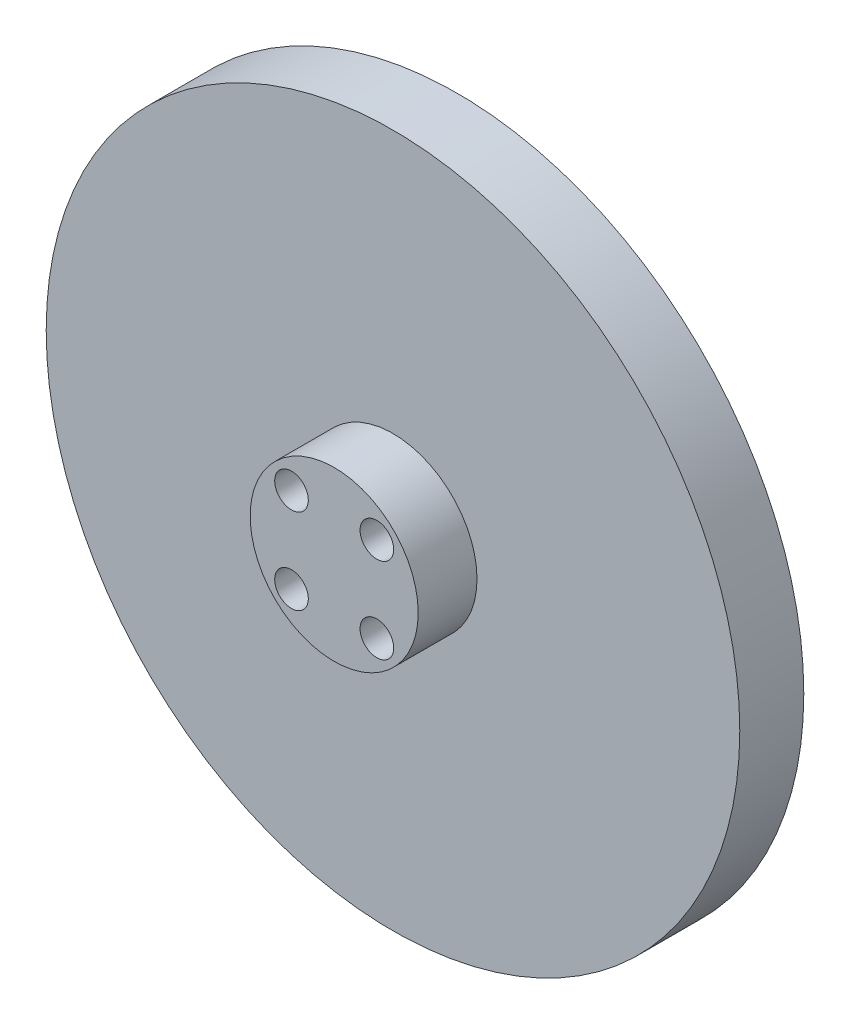
SolidWorks part; units mm, degrees
ref_plane "Front Plane" through (0, 0, 0) normal (0, 0, 1) x (1, 0, 0)
ref_plane "Top Plane" through (0, 0, 0) normal (0, 1, 0) x (1, 0, 0)
ref_plane "Right Plane" through (0, 0, 0) normal (1, 0, 0) x (0, 0, -1)
sketch "Sketch5" plane through (0, 0, 0) normal (0, 0, 1) x (1, 0, 0)
  line L0 (0, 53.4222) -> (0, -51.5958) construction
  line L1 (0, -55) -> (0, 55) construction
  line L2 (-88.0326, 0) -> (87.1194, 0) construction
  line L3 (55, 0) -> (-55, 0) construction
  circle A0 centre (0, 0) radius 41.275
extrude "Boss-Extrude1" add sketch "Sketch5" along normal mid plane 7.62
sketch "Sketch7" plane through (0, 0, 3.81) normal (0, 0, 1) x (1, 0, 0)
  circle A0 centre (0, 0) radius 9.9998
extrude "Boss-Extrude2" add sketch "Sketch7" along normal blind 7
sketch "Sketch8" plane through (0, 0, 10.81) normal (0, 0, 1) x (1, 0, 0)
  circle A0 centre (5.08, 5.08) radius 2
extrude "Cut-Extrude1" cut sketch "Sketch8" against normal through all
pattern_circular "CirPattern1" count 4 over 360 about axis through (0, 0, 0) along (0, 0, 1) of "Cut-Extrude1"
